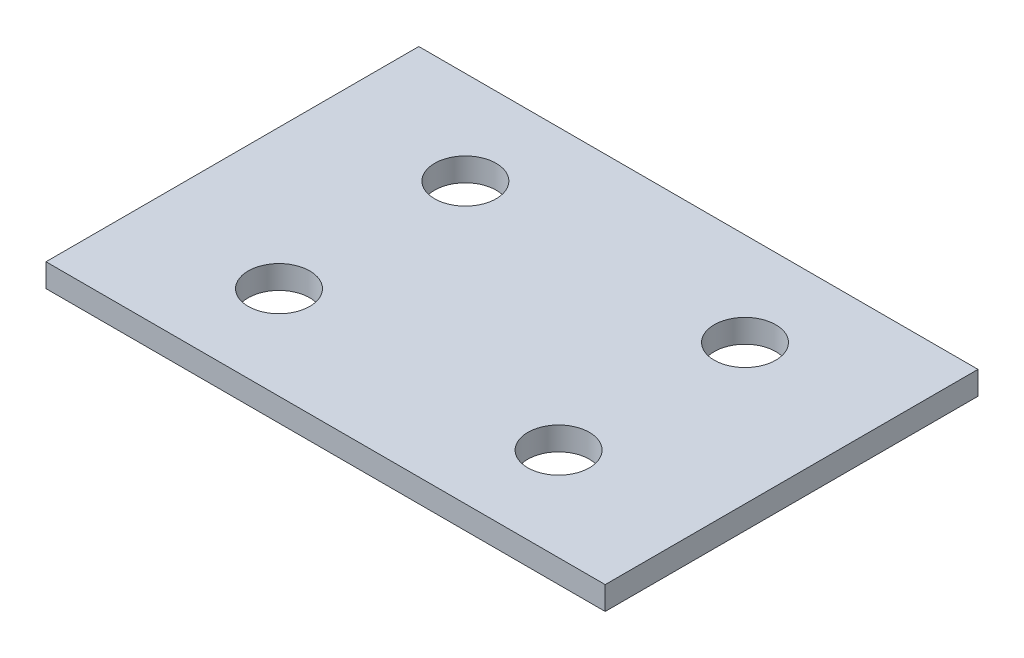
SolidWorks part; units mm, degrees
ref_plane "Front Plane" through (0, 0, 0) normal (0, 0, 1) x (1, 0, 0)
ref_plane "Top Plane" through (0, 0, 0) normal (0, 1, 0) x (1, 0, 0)
ref_plane "Right Plane" through (0, 0, 0) normal (1, 0, 0) x (0, 0, -1)
sketch "Sketch1" plane through (0, 0, 0) normal (0, 1, 0) x (1, 0, 0)
  line L1 (0, 0) -> (76.2, 0)
  line L2 (0, 0) -> (0, 50.8)
  line L3 (0, 50.8) -> (76.2, 50.8)
  line L4 (76.2, 0) -> (76.2, 50.8)
  dimension "D1" = 76.2
  dimension "D2" = 50.8
extrude "Boss-Extrude1" add sketch "Sketch1" along normal blind 3.175
sketch "Sketch3" plane through (0, 3.175, 0) normal (0, 1, 0) x (1, 0, 0)
  line L0 (19.05, 50.8) -> (19.05, 0) construction
  line L1 (76.2, 50.8) -> (0, 50.8) construction
  line L2 (0, 0) -> (76.2, 0) construction
  line L3 (57.15, 50.8) -> (57.15, 0) construction
  line L6 (0, 50.8) -> (0, 0) construction
  line L8 (76.2, 0) -> (76.2, 50.8) construction
  circle A0 centre (19.05, 38.1) radius 4.191
  circle A1 centre (19.05, 12.7) radius 4.191
  circle A2 centre (57.15, 38.1) radius 4.191
  circle A3 centre (57.15, 12.7) radius 4.191
  point P14 (50.0092, 8.7854)
  point P15 (19.1119, 8.7854)
  point P22 (0, 0)
  point P23 (0, 0)
  point P24 (0, 0)
  dimension "D5" = 8.382
  dimension "D1" = 19.05
  dimension "D2" = 19.05
  dimension "D3" = 25.4
  dimension "D4" = 12.7
extrude "Cut-Extrude1" cut sketch "Sketch3" against normal through all
